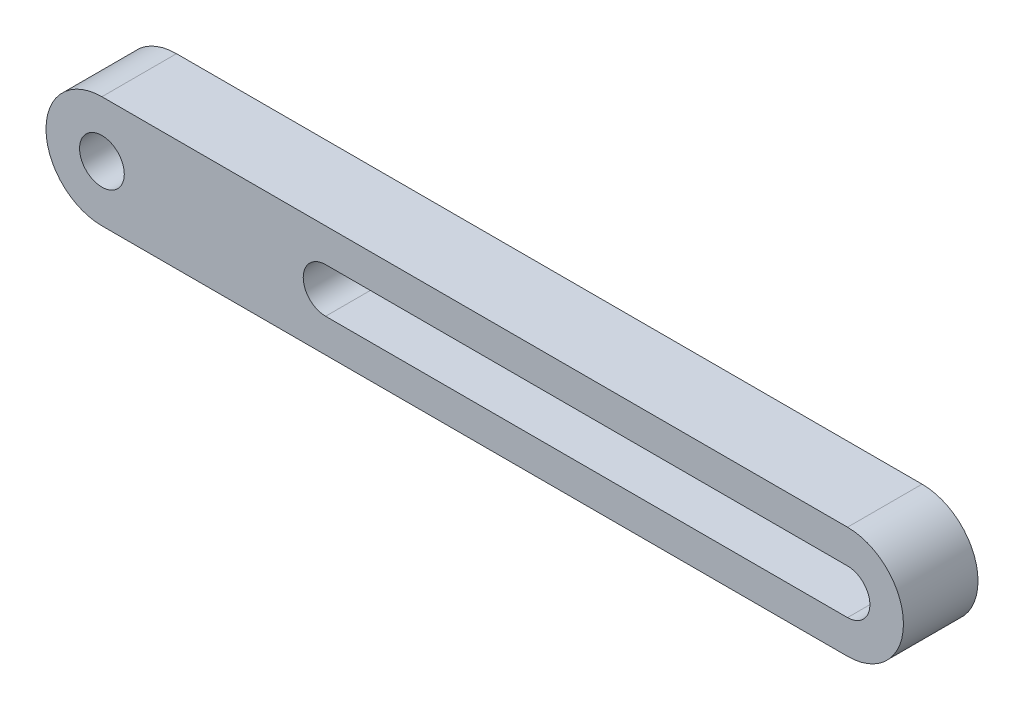
SolidWorks part; units mm, degrees
ref_plane "Alzado" through (0, 0, 0) normal (0, 0, 1) x (1, 0, 0)
ref_plane "Planta" through (0, 0, 0) normal (0, 1, 0) x (1, 0, 0)
ref_plane "Vista lateral" through (0, 0, 0) normal (1, 0, 0) x (0, 0, -1)
sketch "Croquis1" plane through (0, 0, 0) normal (0, 0, 1) x (1, 0, 0)
  line L0 (0, 0) -> (50, 0) construction
  line L1 (0, 3.75) -> (50, 3.75)
  line L2 (0, -3.75) -> (50, -3.75)
  line L3 (15, 0) -> (50, 0) construction
  line L4 (15, 1.5) -> (50, 1.5)
  line L5 (15, -1.5) -> (50, -1.5)
  arc A0 (0, 3.75) -> (0, -3.75) centre (0, 0) ccw
  arc A1 (50, -3.75) -> (50, 3.75) centre (50, 0) ccw
  circle A2 centre (0, 0) radius 1.5
  arc A4 (15, 1.5) -> (15, -1.5) centre (15, 0) ccw
  arc A5 (50, -1.5) -> (50, 1.5) centre (50, 0) ccw
  point P3 (25, 0)
  point P13 (32.5, 0)
  dimension "D3" = 3
  dimension "D4" = 1.5
  dimension "D1" = 50
  dimension "D2" = 7.5
  dimension "D5" = 15
extrude "Saliente-Extruir1" add sketch "Croquis1" along normal blind 5
ref_plane "Plane1" through (0, 0, 2.5) normal (0, 0, 1) x (1, 0, 0)
sketch "Sketch1" plane through (0, 0, 2.5) normal (0, 0, 1) x (1, 0, 0)
  line L0 (15, 1.5) -> (15, -1.5) construction
  line L1 (50, 1.5) -> (50, -1.5) construction
  line L2 (15, 0) -> (50, 0)
